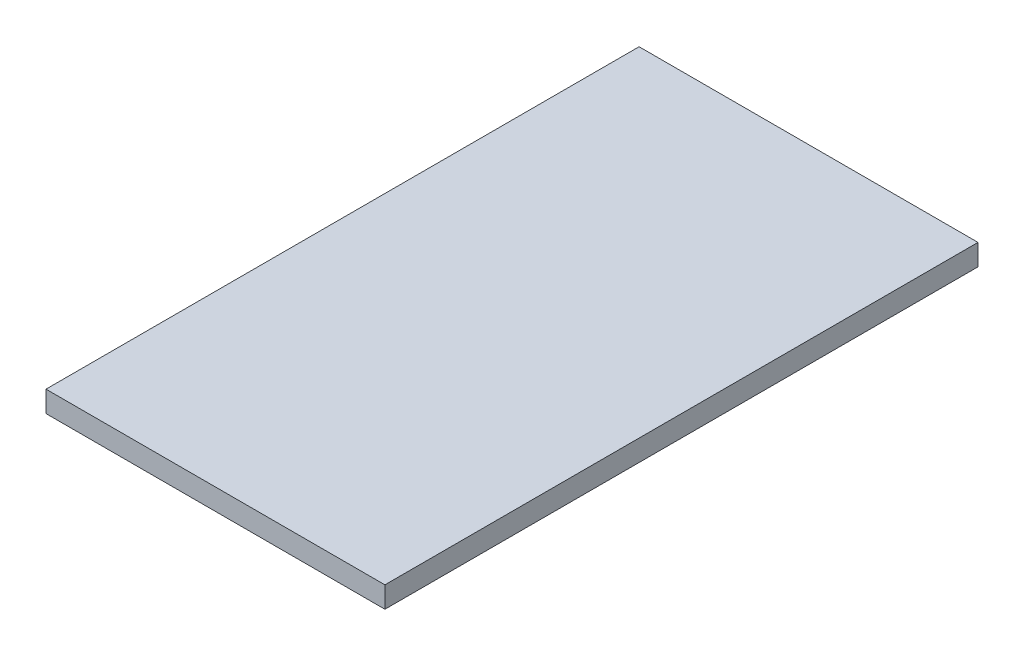
SolidWorks part; units mm, degrees
ref_plane "Front Plane" through (0, 0, 0) normal (0, 0, 1) x (1, 0, 0)
ref_plane "Top Plane" through (0, 0, 0) normal (0, 1, 0) x (1, 0, 0)
ref_plane "Right Plane" through (0, 0, 0) normal (1, 0, 0) x (0, 0, -1)
sketch "Sketch1" plane through (0, 0, 0) normal (0, 1, 0) x (1, 0, 0)
  line L1 (0, 0) -> (304.8, 0)
  line L2 (0, 0) -> (0, 533.4)
  line L3 (0, 533.4) -> (304.8, 533.4)
  line L4 (304.8, 0) -> (304.8, 533.4)
  dimension "D1" = 304.8
  dimension "D2" = 533.4
extrude "Boss-Extrude1" add sketch "Sketch1" along normal blind 19.05
